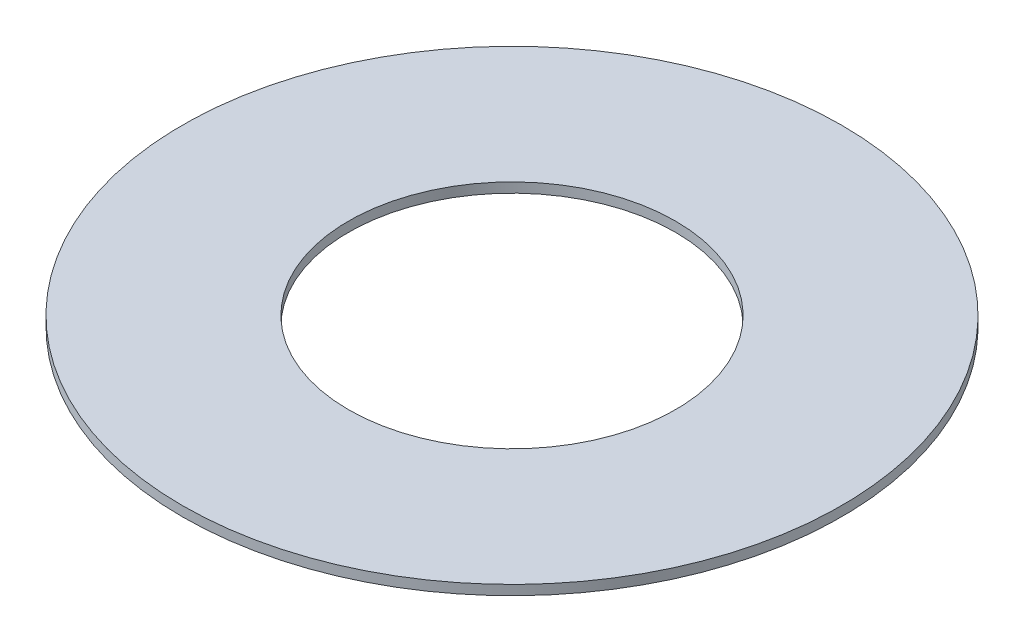
SolidWorks part; units mm, degrees
material "Plain Carbon Steel"
ref_plane "Front Plane" through (0, 0, 0) normal (0, 0, 1) x (1, 0, 0)
ref_plane "Top Plane" through (0, 0, 0) normal (0, 1, 0) x (1, 0, 0)
ref_plane "Right Plane" through (0, 0, 0) normal (1, 0, 0) x (0, 0, -1)
sketch "Sketch1" plane through (0, 0, 0) normal (0, 1, 0) x (1, 0, 0)
  circle A0 centre (0, 0) radius 67.48
  circle A1 centre (0, 0) radius 33.47
  dimension "D1" = 134.96
  dimension "D2" = 66.94
extrude "Boss-Extrude1" add sketch "Sketch1" along normal blind 2
